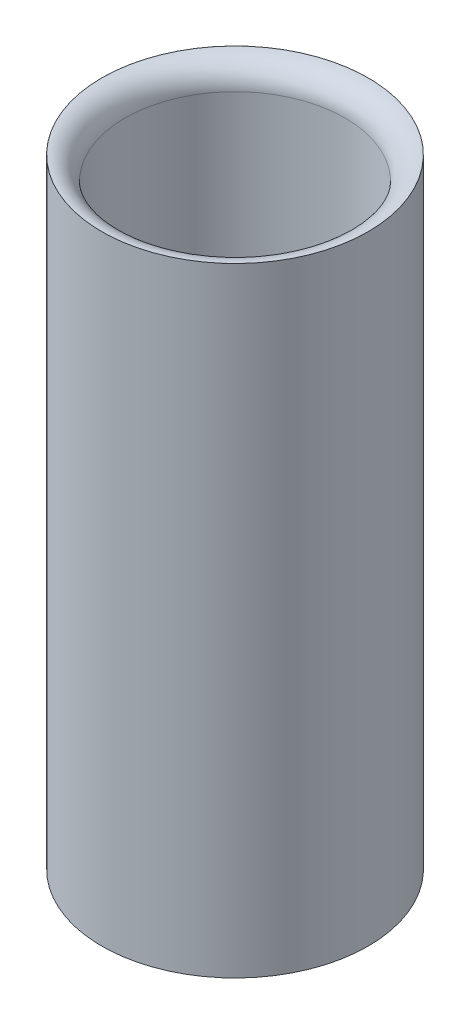
SolidWorks part; units mm, degrees
ref_plane "Płaszczyzna przednia" through (0, 0, 0) normal (0, 0, 1) x (1, 0, 0)
ref_plane "Płaszczyzna górna" through (0, 0, 0) normal (0, 1, 0) x (1, 0, 0)
ref_plane "Płaszczyzna prawa" through (0, 0, 0) normal (1, 0, 0) x (0, 0, -1)
sketch "Szkic1" plane through (0, 0, 0) normal (0, 0, 1) x (1, 0, 0)
  line L0 (0, -51.8535) -> (0, 61.6013) construction
  line L1 (-19.02, -51.2035) -> (-22.04, -51.2035)
  line L2 (-23.04, -50.2035) -> (-23.04, 55.7965)
  line L3 (0, -50.3715) -> (0, -41.4115)
  line L4 (0, -41.4115) -> (-19.02, -41.4115)
  line L5 (-19.02, -41.4115) -> (-19.02, 51.7965)
  line L6 (-23.02, 55.7965) -> (-23.04, 55.7965)
  line L7 (-22.04, -51.2035) -> (-22.04, 51.1965) construction
  line L8 (-22.04, 51.1965) -> (-19.02, 51.1965) construction
  line L9 (-22.04, -51.2035) -> (-23.04, -51.2035)
  line L10 (-19.02, -41.4115) -> (-19.02, -56.7937) construction
  line L11 (-19.02, -51.2035) -> (-9.51, -50.3715)
  line L12 (-9.51, -50.3715) -> (0, -50.3715)
  line L13 (-23.04, -51.2035) -> (-23.04, -50.2035)
  arc A1 (-19.02, 51.7965) -> (-23.02, 55.7965) centre (-23.02, 51.7965) ccw
  dimension "D6" = 4
  dimension "D2" = 9.51
  dimension "D3" = 19.02
  dimension "D4" = 23.04
  dimension "D5" = 107
  dimension "D7" = 102.4
  dimension "D8" = 8.96
  dimension "D9" = 5
revolve "Obrót1" add sketch "Szkic1" angle 360 about L0
